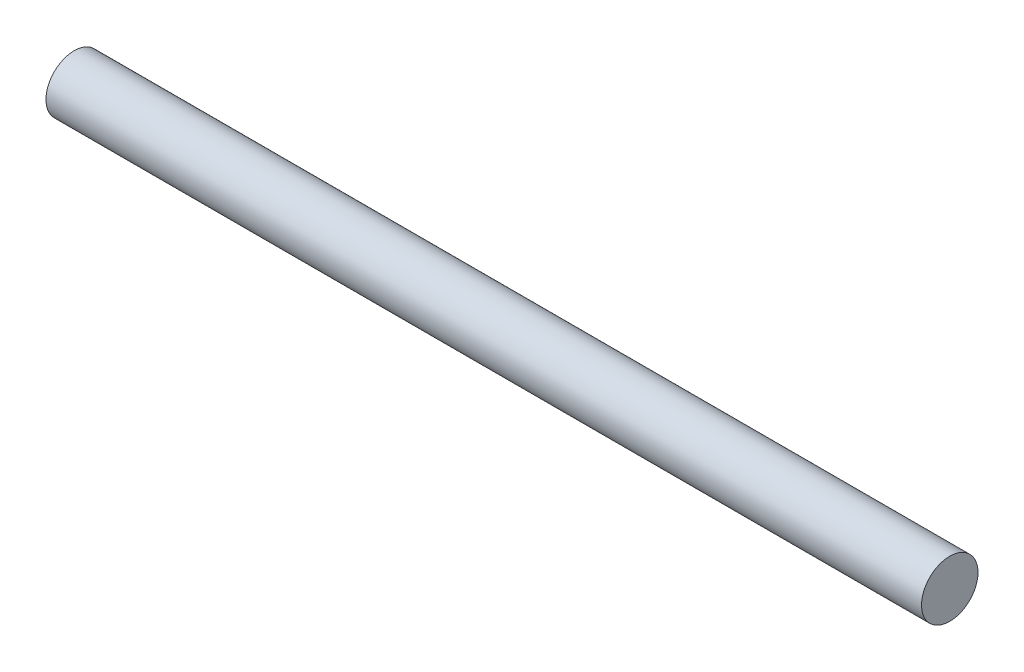
SolidWorks part; units mm, degrees
ref_plane "Alzado" through (0, 0, 0) normal (0, 0, 1) x (1, 0, 0)
ref_plane "Planta" through (0, 0, 0) normal (0, 1, 0) x (1, 0, 0)
ref_plane "Vista lateral" through (0, 0, 0) normal (1, 0, 0) x (0, 0, -1)
sketch "Croquis1" plane through (0, 0, 0) normal (1, 0, 0) x (0, 0, -1)
  circle A0 centre (0, 0) radius 10
  dimension "D1" = 20
extrude "Saliente-Extruir1" add sketch "Croquis1" along normal blind 310
